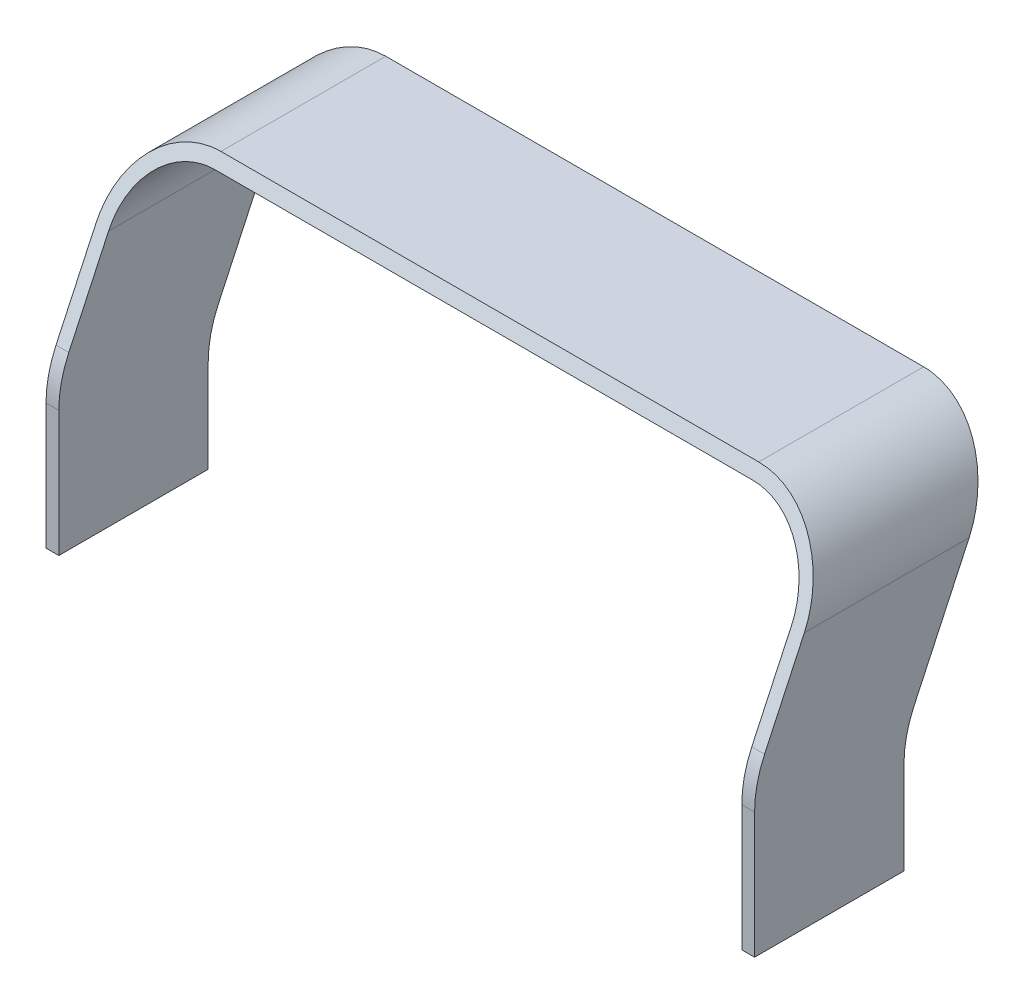
SolidWorks part; units mm, degrees
ref_plane "Front Plane" through (0, 0, 0) normal (0, 0, 1) x (1, 0, 0)
ref_plane "Top Plane" through (0, 0, 0) normal (0, 1, 0) x (1, 0, 0)
ref_plane "Right Plane" through (0, 0, 0) normal (1, 0, 0) x (0, 0, -1)
sketch "Sketch1" plane through (0, 0, 0) normal (0, 0, 1) x (1, 0, 0)
  line L0 (-83, 5) -> (-83, 65)
  line L1 (-63, 85) -> (63, 85)
  line L2 (83, 65) -> (83, 5)
  line L3 (-80, 5) -> (-80, 65)
  line L4 (-63, 82) -> (63, 82)
  line L5 (80, 65) -> (80, 5)
  line L6 (-83, 5) -> (-80, 5)
  line L7 (80, 5) -> (83, 5)
  arc A0 (63, 85) -> (83, 65) centre (63, 65) cw
  arc A1 (-83, 65) -> (-63, 85) centre (-63, 65) cw
  arc A2 (-80, 65) -> (-63, 82) centre (-63, 65) cw
  arc A3 (63, 82) -> (80, 65) centre (63, 65) cw
  dimension "D2" = 20
  dimension "D1" = 80
  dimension "D3" = 3
extrude "Boss-Extrude1" add sketch "Sketch1" along normal blind 70
sketch "Sketch2" plane through (-83, 0, 0) normal (-1, 0, 0) x (0, 0, 1)
  line L0 (49.0162, 85) -> (70, 40)
  line L1 (70, 85) -> (0, 85) construction
  line L2 (70, 65) -> (70, 5) construction
  line L3 (10.3979, 85) -> (35, 32.2407)
  line L4 (35, 32.2407) -> (35, 4.8709)
  line L5 (35, 4.8709) -> (0, 4.8709)
  line L6 (0, 0) -> (0, 30) construction
  line L7 (0, 4.8709) -> (0, 85)
  line L8 (0, 85) -> (10.3979, 85)
  line L9 (49.0162, 85) -> (70, 85)
  line L10 (70, 85) -> (70, 40)
  dimension "D1" = 25
  dimension "D2" = 45
  dimension "D3" = 35
  dimension "D4" = 35
extrude "Cut-Extrude1" cut sketch "Sketch2" against normal through all
fillet "Fillet1" radius 25 4 edges at (81.5, 32.2407, 35) (-81.5, 32.2407, 35) (81.5, 40, 70) (-81.5, 40, 70)
